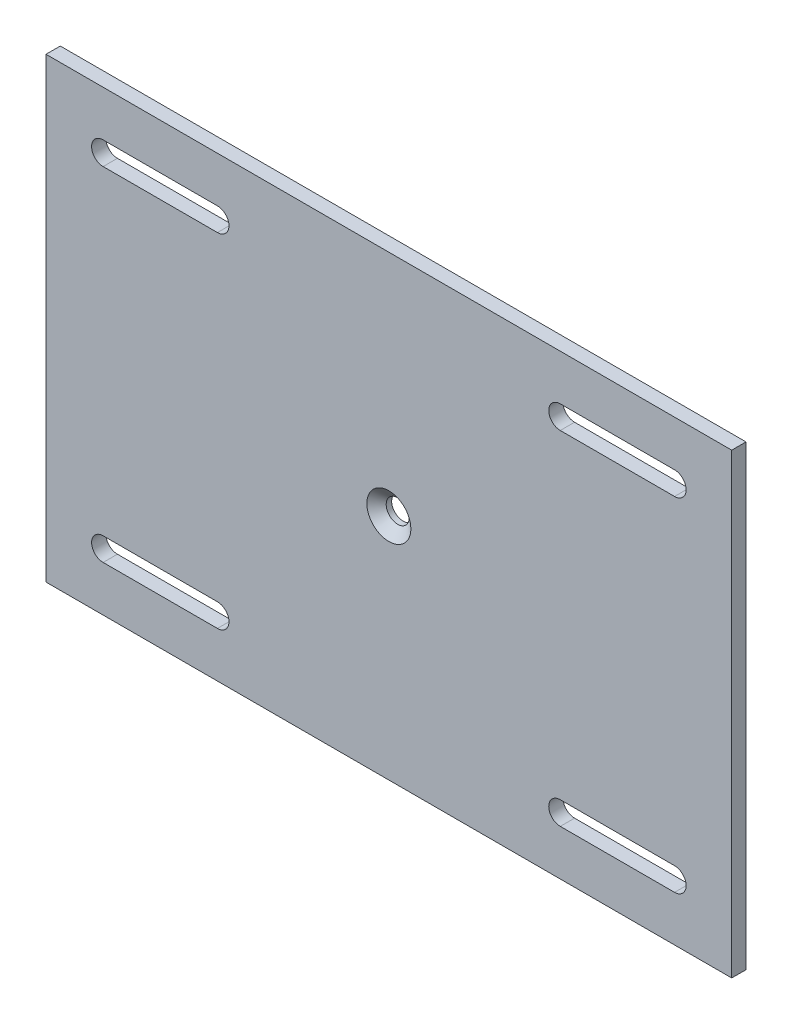
SolidWorks part; units mm, degrees
ref_plane "Front Plane" through (0, 0, 0) normal (0, 0, 1) x (1, 0, 0)
ref_plane "Top Plane" through (0, 0, 0) normal (0, 1, 0) x (1, 0, 0)
ref_plane "Right Plane" through (0, 0, 0) normal (1, 0, 0) x (0, 0, -1)
sketch "Sketch1" plane through (0, 0, 0) normal (0, 0, 1) x (1, 0, 0)
  line L1 (-76.2, -50.8) -> (76.2, -50.8)
  line L2 (-76.2, -50.8) -> (-76.2, 50.8)
  line L3 (-76.2, 50.8) -> (76.2, 50.8)
  line L4 (76.2, -50.8) -> (76.2, 50.8)
  line L5 (-76.2, -50.8) -> (76.2, 50.8) construction
  line L6 (-76.2, 50.8) -> (76.2, -50.8) construction
  point P0 (0, 0)
  dimension "D1" = 152.4
  dimension "D2" = 101.6
extrude "Boss-Extrude1" add sketch "Sketch1" along normal blind 3.175
sketch "Sketch2" plane through (0, 0, 3.175) normal (0, 0, 1) x (1, 0, 0)
  line L0 (-63.5, 38.1) -> (-38.1, 38.1) construction
  line L1 (-63.5, 40.6659) -> (-38.1, 40.6659)
  line L2 (-63.5, 35.5341) -> (-38.1, 35.5341)
  line L3 (76.2, 50.8) -> (-76.2, 50.8) construction
  line L4 (-76.2, 50.8) -> (-76.2, -50.8) construction
  arc A0 (-63.5, 40.6659) -> (-63.5, 35.5341) centre (-63.5, 38.1) ccw
  arc A1 (-38.1, 35.5341) -> (-38.1, 40.6659) centre (-38.1, 38.1) ccw
  point P2 (-50.8, 38.1)
  dimension "D1" = 25.4
  dimension "D2" = 12.7
  dimension "D3" = 25.4
extrude "Cut-Extrude1" cut sketch "Sketch2" against normal through all and the other way through all
mirror "Mirror1" about plane through (0, 0, 0) normal (1, 0, 0) of "Cut-Extrude1"
mirror "Mirror2" about plane through (0, 0, 0) normal (0, 1, 0) of "Mirror1", "Cut-Extrude1"
hole_wizard "CSK for #10 Flat Head Machine Screw (100)1" positions "Sketch3" profile "Sketch5" countersink size "#10" standard "ANSI Inch" end condition through all
sketch "Sketch3" plane through (0, 0, 3.175) normal (0, 0, 1) x (1, 0, 0)
  point P0 (0, 0)
sketch "Sketch5" plane through (0, 0, 3.175) normal (1, 0, 0) x (0, -1, 0)
  line L0 (0, 0) -> (0, 3.175)
  line L1 (0, 3.175) -> (2.5527, 3.175)
  line L2 (2.5527, 3.175) -> (2.5527, 1.9608)
  line L3 (2.5527, 1.9608) -> (4.8895, 0)
  line L5 (4.8895, 0) -> (0, 0)
  line L6 (-2.5527, 1.9608) -> (-4.8895, 0) construction
  line L11 (0, -6.35) -> (0, 107.95) construction
  dimension "Thru Hole Dia." = 5.1054
  dimension "Thru Hole Depth" = 3.175
  dimension "Near C'Sink Dia." = 9.779
  dimension "Near C'Sink Angle" = 100
